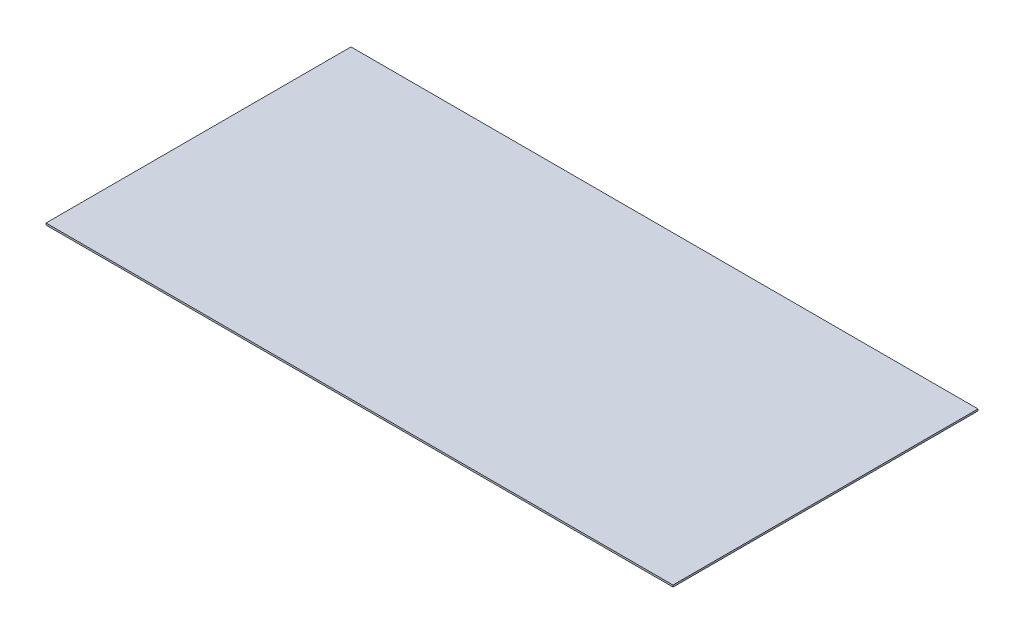
SolidWorks part; units mm, degrees
ref_plane "Front Plane" through (0, 0, 0) normal (0, 0, 1) x (1, 0, 0)
ref_plane "Top Plane" through (0, 0, 0) normal (0, 1, 0) x (1, 0, 0)
ref_plane "Right Plane" through (0, 0, 0) normal (1, 0, 0) x (0, 0, -1)
sketch "Sketch1" plane through (0, 0, 0) normal (0, 1, 0) x (1, 0, 0)
  line L1 (0, 0) -> (-1028, 0)
  line L2 (0, 0) -> (0, -500)
  line L3 (0, -500) -> (-1028, -500)
  line L4 (-1028, 0) -> (-1028, -500)
  dimension "D1" = 1028
  dimension "D2" = 500
extrude "Boss-Extrude1" add sketch "Sketch1" along normal blind 3
